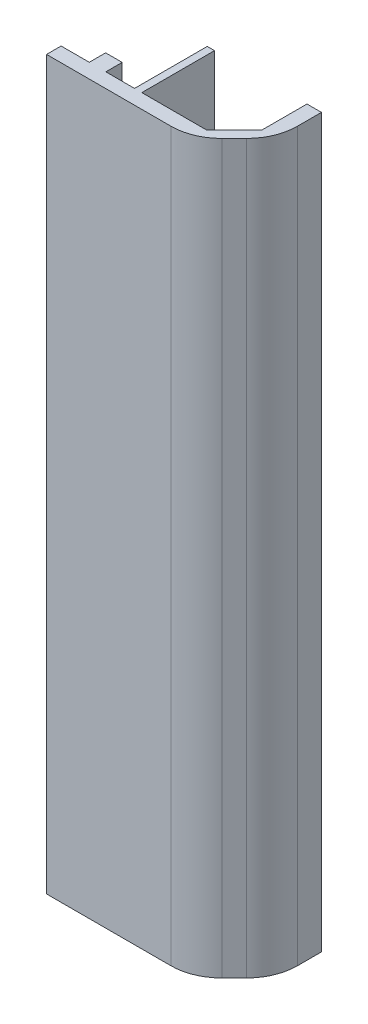
SolidWorks part; units mm, degrees
ref_plane "前基準面" through (0, 0, 0) normal (0, 0, 1) x (1, 0, 0)
ref_plane "上基準面" through (0, 0, 0) normal (0, 1, 0) x (1, 0, 0)
ref_plane "右基準面" through (0, 0, 0) normal (1, 0, 0) x (0, 0, -1)
sketch "草圖1" plane through (0, 0, 0) normal (0, 1, 0) x (1, 0, 0)
  line L0 (-27.5017, 6.8593) -> (-22.9517, 6.8593)
  line L1 (-22.9517, 6.8593) -> (-22.9517, 2.3593)
  line L2 (-22.9517, 2.3593) -> (4.7983, 2.3593)
  line L3 (4.7983, 2.3593) -> (12.3816, 9.9426)
  line L4 (12.3816, 9.9426) -> (12.3816, 22.3593)
  line L5 (-27.5017, 6.8593) -> (-27.5017, 2.3593)
  line L6 (-27.5017, 2.3593) -> (-35.2517, 2.3593)
  line L7 (-35.2517, 2.3593) -> (-35.2517, -1.6407)
  line L8 (-35.2517, -1.6407) -> (4.7783, -1.6407)
  line L12 (4.7783, -1.6407) -> (16.3616, 9.9426)
  line L13 (12.3816, 22.3593) -> (16.3616, 22.3593)
  line L14 (16.3616, 22.3593) -> (16.3616, 9.9426)
  dimension "D1" = 4.55
  dimension "D2" = 4.5
  dimension "D3" = 4
  dimension "D4" = 4
  dimension "D5" = 7.75
  dimension "D6" = 27.75
  dimension "D7" = 20
extrude "填料-伸長1" add sketch "草圖1" along normal blind 200
fillet "圓角1" radius 14 2 edges at (4.7783, 100, 1.6407) (16.3616, 100, -9.9426)
sketch "草圖2" plane through (0, 0, -2.3593) normal (0, 0, -1) x (-1, 0, 0)
  line L0 (-4.7983, 200) -> (22.9517, 200) construction
  line L1 (13.0517, 200) -> (15.0517, 200)
  line L2 (13.0517, 200) -> (13.0517, 0)
  line L3 (13.0517, 0) -> (15.0517, 0)
  line L4 (15.0517, 200) -> (15.0517, 0)
  line L5 (-4.7983, 0) -> (22.9517, 0) construction
  line L6 (35.2517, 200) -> (35.2517, 0) construction
  dimension "D1" = 20.2
  dimension "D2" = 2
extrude "填料-伸長2" add sketch "草圖2" along normal blind 20
